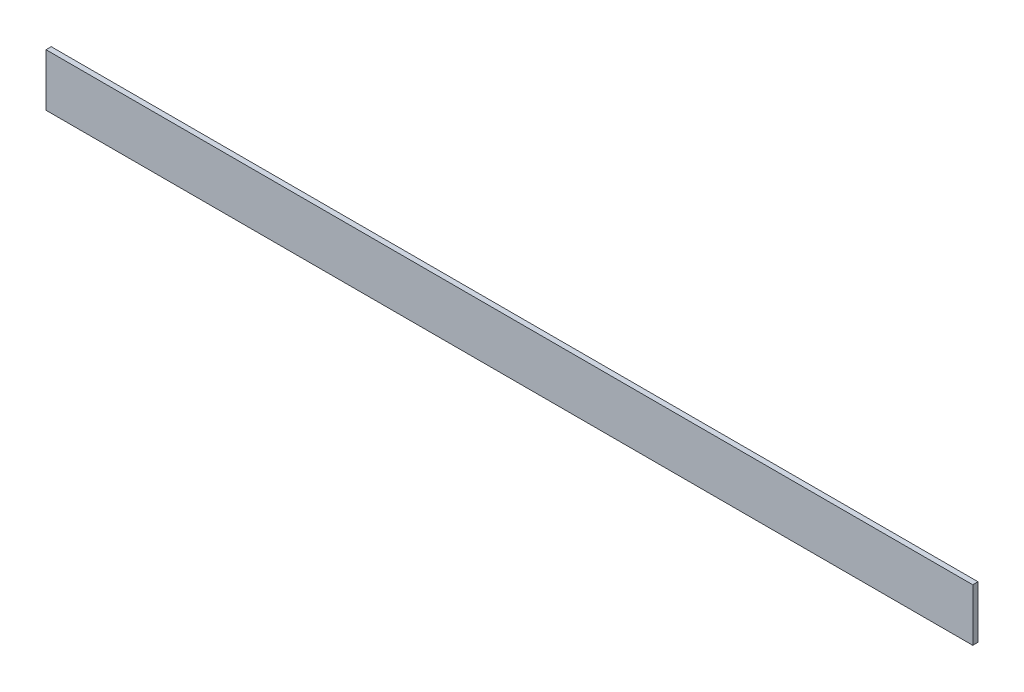
SolidWorks part; units mm, degrees
ref_plane "Спереди" through (0, 0, 0) normal (0, 0, 1) x (1, 0, 0)
ref_plane "Сверху" through (0, 0, 0) normal (0, 1, 0) x (1, 0, 0)
ref_plane "Справа" through (0, 0, 0) normal (1, 0, 0) x (0, 0, -1)
sketch "Эскиз1" plane through (0, 0, 0) normal (1, 0, 0) x (0, 0, -1)
  line L0 (0, 30) -> (0, 0)
  line L1 (0, 0) -> (30, 0)
extrude "Вытянуть-Тонкостенный1" add sketch "Эскиз1" along normal blind 530 thin thin type one direction reverse wall 3
sketch "Эскиз2" plane through (0, 0, 0) normal (0, -1, 0) x (1, 0, 0)
  line L1 (530, -30) -> (500, -30)
  line L2 (530, -30) -> (530, -3)
  line L3 (530, -3) -> (500, -3)
  line L4 (500, -30) -> (500, -3)
  line L5 (0, -30) -> (30, -30)
  line L6 (0, -30) -> (0, -3)
  line L7 (0, -3) -> (30, -3)
  line L8 (30, -30) -> (30, -3)
extrude "Вырез-Вытянуть1" cut sketch "Эскиз2" against normal through all
